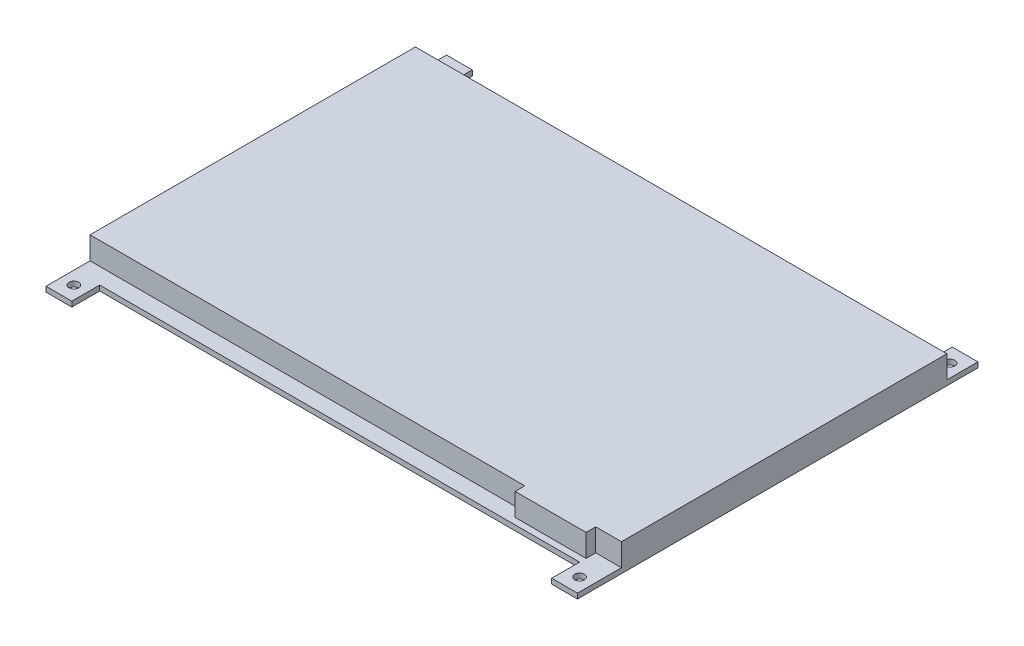
SolidWorks part; units mm, degrees
ref_plane "Front Plane" through (0, 0, 0) normal (0, 0, 1) x (1, 0, 0)
ref_plane "Top Plane" through (0, 0, 0) normal (0, 1, 0) x (1, 0, 0)
ref_plane "Right Plane" through (0, 0, 0) normal (1, 0, 0) x (0, 0, -1)
sketch "Sketch1" plane through (0, 0, 0) normal (0, 1, 0) x (1, 0, 0)
  line L0 (-159.3877, -19.805) -> (-167.3877, -19.805) construction
  line L1 (-167.3877, 87.155) -> (-2.4877, 87.155) construction
  line L2 (-167.3877, 87.155) -> (-167.3877, -19.805)
  line L3 (-167.3877, -19.805) -> (-2.4877, -19.805) construction
  line L4 (-2.4877, 87.155) -> (-2.4877, -19.805)
  line L5 (-167.3877, 87.155) -> (-2.4877, -19.805) construction
  line L6 (-167.3877, -19.805) -> (-2.4877, 87.155) construction
  line L7 (-2.4877, -19.805) -> (-10.4877, -19.805) construction
  line L8 (-2.4877, -19.805) -> (-2.4877, -28.46) construction
  line L9 (-2.4877, -28.46) -> (-10.4877, -28.46) construction
  line L10 (-10.4877, -19.805) -> (-10.4877, -28.46) construction
  line L11 (-159.3877, -19.805) -> (-159.3877, -28.46) construction
  line L12 (-159.3877, -28.46) -> (-167.3877, -28.46) construction
  line L13 (-167.3877, -19.805) -> (-167.3877, -28.46) construction
  line L14 (-159.3877, 95.81) -> (-167.3877, 95.81) construction
  line L15 (-159.3877, 95.81) -> (-159.3877, 87.155) construction
  line L16 (-159.3877, 87.155) -> (-167.3877, 87.155) construction
  line L17 (-167.3877, 95.81) -> (-167.3877, 87.155) construction
  line L18 (-2.4877, 95.81) -> (-10.4877, 95.81) construction
  line L19 (-2.4877, 95.81) -> (-2.4877, 87.155) construction
  line L20 (-2.4877, 87.155) -> (-10.4877, 87.155) construction
  line L21 (-10.4877, 95.81) -> (-10.4877, 87.155) construction
  line L22 (-84.9377, 87.155) -> (-84.9377, -19.805) construction
  line L23 (-167.3877, 87.155) -> (-167.3877, 95.81)
  line L24 (-167.3877, 95.81) -> (-159.3877, 95.81)
  line L25 (-156.8553, -27.5518) -> (-156.8553, -27.7405) construction
  line L26 (-167.3877, 33.675) -> (-2.4877, 33.675) construction
  line L27 (-159.3877, 95.81) -> (-159.3877, 87.155)
  line L28 (-159.3877, 87.155) -> (-10.4877, 87.155)
  line L29 (-10.4877, 87.155) -> (-10.4877, 95.81)
  line L30 (-10.4877, 95.81) -> (-2.4877, 95.81)
  line L31 (-2.4877, 95.81) -> (-2.4877, 87.155)
  line L32 (-2.4877, -19.805) -> (-2.4877, -28.46)
  line L33 (-2.4877, -28.46) -> (-10.4877, -28.46)
  line L34 (-10.4877, -28.46) -> (-10.4877, -19.805)
  line L35 (-10.4877, -19.805) -> (-159.3877, -19.805)
  line L36 (-159.3877, -19.805) -> (-159.3877, -28.46)
  line L37 (-159.3877, -28.46) -> (-167.3877, -28.46)
  line L38 (-167.3877, -28.46) -> (-167.3877, -19.805)
  circle A3 centre (-6.4877, -23.805) radius 1.5
  circle A4 centre (-163.3877, -23.805) radius 1.5
  circle A6 centre (-6.4877, 91.155) radius 1.5
  circle A7 centre (-163.3877, 91.155) radius 1.5
  point P0 (-84.9377, 33.675)
  dimension "D11" = 114.96
  dimension "D12" = 3
  dimension "D15" = 3
  dimension "D13" = 156.9
  dimension "D1" = 164.9
  dimension "D2" = 106.96
  dimension "D3" = 8.655
  dimension "D4" = 8
  dimension "D5" = 8.655
  dimension "D6" = 8
  dimension "D7" = 8.655
  dimension "D8" = 8
  dimension "D9" = 8.655
  dimension "D10" = 8
  dimension "D14" = 156.9
  dimension "D16" = 114.96
extrude "Boss-Extrude1" add sketch "Sketch1" along normal blind 1.6
sketch "Sketch2" plane through (0, 1.6, 0) normal (0, 1, 0) x (1, 0, 0)
  line L0 (-2.4877, -28.46) -> (-2.4877, 95.81) construction
  line L1 (-167.3877, 86.155) -> (-2.4877, 86.155)
  line L2 (-167.3877, 86.155) -> (-167.3877, -14.805)
  line L3 (-167.3877, -14.805) -> (-2.4877, -14.805) construction
  line L4 (-2.4877, 86.155) -> (-2.4877, -14.805)
  line L5 (-167.3877, 95.81) -> (-167.3877, -28.46) construction
  line L7 (-159.3877, -19.805) -> (-10.4877, -19.805) construction
  line L8 (-167.3877, -14.805) -> (-32.4877, -14.805)
  line L9 (-32.4877, -14.805) -> (-32.4877, -17.805)
  line L10 (-32.4877, -17.805) -> (-10.4877, -17.805)
  line L11 (-10.4877, -17.805) -> (-10.4877, -14.805)
  line L12 (-10.4877, -14.805) -> (-2.4877, -14.805)
  line L13 (-10.4877, 87.155) -> (-159.3877, 87.155) construction
  dimension "D1" = 1
  dimension "D2" = 5
  dimension "D3" = 8
  dimension "D4" = 22
  dimension "D5" = 3
extrude "Boss-Extrude2" add sketch "Sketch2" along normal blind 7
